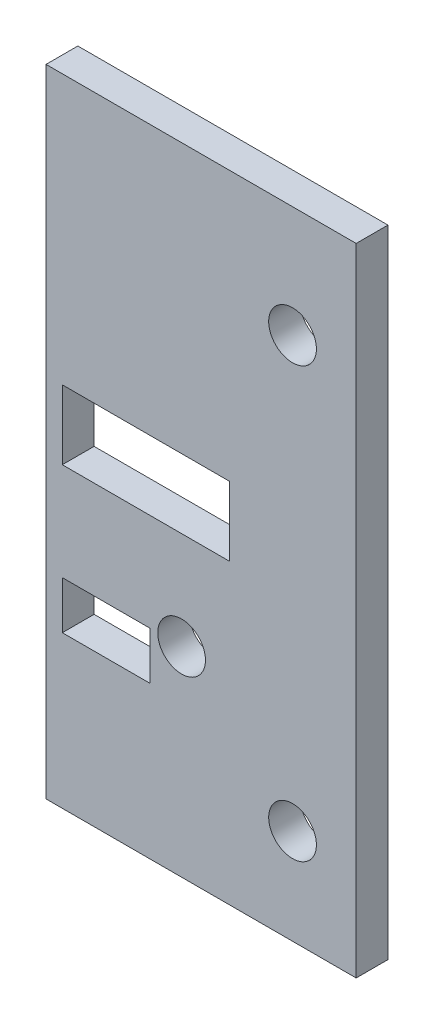
SolidWorks part; units mm, degrees
ref_plane "Front Plane" through (0, 0, 0) normal (0, 0, 1) x (1, 0, 0)
ref_plane "Top Plane" through (0, 0, 0) normal (0, 1, 0) x (1, 0, 0)
ref_plane "Right Plane" through (0, 0, 0) normal (1, 0, 0) x (0, 0, -1)
sketch "Sketch1" plane through (0, 0, 0) normal (0, 0, 1) x (1, 0, 0)
  line L1 (9.75, -20) -> (-9.75, -20)
  line L2 (9.75, -20) -> (9.75, 20)
  line L3 (9.75, 20) -> (-9.75, 20)
  line L4 (-9.75, -20) -> (-9.75, 20)
  line L5 (9.75, -20) -> (-9.75, 20) construction
  line L6 (9.75, 20) -> (-9.75, -20) construction
  point P0 (0, 0)
  dimension "D1" = 40
  dimension "D2" = 19.5
extrude "Boss-Extrude1" add sketch "Sketch1" along normal blind 2
sketch "Sketch2" plane through (0, 0, 2) normal (0, 0, 1) x (1, 0, 0)
  line L0 (1.7735, -10.436) -> (-8.7265, -10.436)
  line L1 (1.7735, -10.436) -> (1.7735, 3.064)
  line L2 (1.7735, 3.064) -> (-8.7265, 3.064)
  line L3 (-8.7265, -10.436) -> (-8.7265, 3.064)
  line L4 (1.7735, -10.436) -> (-8.7265, 3.064) construction
  line L5 (1.7735, 3.064) -> (-8.7265, -10.436) construction
  line L6 (1.7735, -1.2896) -> (-8.7265, -1.2896)
  line L7 (1.7735, -1.2896) -> (1.7735, 3.064)
  line L8 (1.7735, 3.064) -> (-8.7265, 3.064)
  line L9 (-8.7265, -1.2896) -> (-8.7265, 3.064)
  line L10 (1.7735, -1.2896) -> (-8.7265, 3.064) construction
  line L11 (1.7735, 3.064) -> (-8.7265, -1.2896) construction
  line L12 (-3.2265, -10.436) -> (-8.7265, -10.436)
  line L13 (-3.2265, -10.436) -> (-3.2265, -7.436)
  line L14 (-3.2265, -7.436) -> (-8.7265, -7.436)
  line L15 (-8.7265, -10.436) -> (-8.7265, -7.436)
  line L16 (-3.2265, -10.436) -> (-8.7265, -7.436) construction
  line L17 (-3.2265, -7.436) -> (-8.7265, -10.436) construction
  circle A0 centre (-1.2265, -7.436) radius 1.5
  point P0 (-3.4765, -3.686)
  point P5 (-3.4765, 0.8872)
  point P6 (-5.9765, -8.936)
extrude "Cut-Extrude1" cut sketch "Sketch2" against normal blind 2 contours A0 | L13 L14 L3 L0 | L6 L1 L2 L3
sketch "Sketch3" plane through (0, 0, 2) normal (0, 0, 1) x (1, 0, 0)
  line L0 (-9.75, -20) -> (9.75, -20) construction
  line L1 (9.75, -20) -> (9.75, 20) construction
  circle A0 centre (5.75, -14) radius 1.5
  circle A1 centre (5.75, 13) radius 1.5
  point P10 (6.1523, -13.9788)
  point P11 (9.75, 13.7596)
  dimension "D1" = 3
  dimension "D2" = 3
  dimension "D5" = 4
  dimension "D6" = 27
  dimension "D3" = 6
  dimension "D4" = 4
extrude "Cut-Extrude2" cut sketch "Sketch3" against normal blind 2
